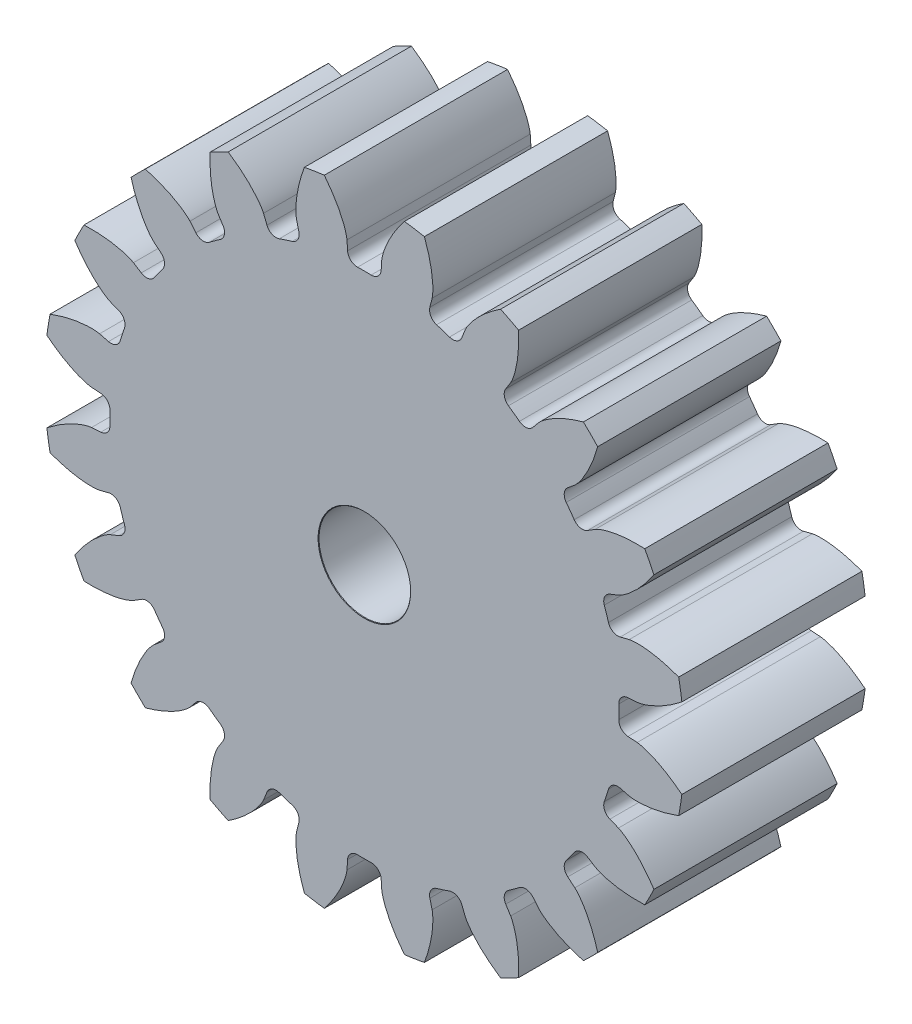
SolidWorks part; units mm, degrees
ref_plane "Front Plane" through (0, 0, 0) normal (0, 0, 1) x (1, 0, 0)
ref_plane "Top Plane" through (0, 0, 0) normal (0, 1, 0) x (1, 0, 0)
ref_plane "Right Plane" through (0, 0, 0) normal (1, 0, 0) x (0, 0, -1)
sketch "Sketch1" plane through (0, 0, 0) normal (0, 0, 1) x (1, 0, 0)
  line L0 (0, 0) -> (0, 15.875) construction
  line L1 (-5.1021, 17.732) -> (5.1021, 14.018) construction
  circle A0 centre (0, 0) radius 13.8906 construction
  circle A1 centre (0, 0) radius 17.4625 construction
  circle A2 centre (0, 0) radius 15.875 construction
  circle A3 centre (0, 0) radius 14.9176 construction
  point P8 (203.2, 0)
  point P13 (254, 0)
  dimension "OD | Outside Diameter" = 34.925
  dimension "Root Diameter" = 27.7812
  dimension "Gear Pitch Diameter" = 31.75
  dimension "Base Diameter" = 29.8352
  dimension "Pressure Angle" = 20
  dimension "Number of Teeth" = 508
  dimension "Gear Pitch | Diametral Pitch" = 406.4
sketch "Sketch2" plane through (0, 0, 0) normal (1, 0, 0) x (0, 0, -1)
  line L0 (-5, 0) -> (5, 0) construction
  point P2 (12.4625, 0)
  point P5 (21.1937, 0)
  point P6 (-12.4625, 0)
  dimension "Length" = 10
  dimension "D1" = 17.4625
  dimension "D2" = 26.1937
  dimension "D3" = 17.4625
sketch "Sketch3" plane through (0, 0, 0) normal (0, 0, 1) x (1, 0, 0)
  circle A0 centre (0, 0) radius 17.4625
  circle A1 centre (0, 0) radius 17.4625 construction
extrude "Boss-Extrude1" add sketch "Sketch3" against normal up to vertex (5 mm away) and the other way up to vertex (5 mm away) up to point (0, 0, -5) other way up to point (0, 0, 5)
sketch "Sketch4" plane through (0, 0, 0) normal (0, 0, 1) x (1, 0, 0)
  line L0 (0, 0) -> (13.8625, 0.8833) construction
  line L2 (0, 0) -> (13.8625, -0.8833) construction
  line L4 (13.8625, 0.8833) -> (14.8874, 0.9486)
  line L5 (14.8874, -0.9486) -> (13.8625, -0.8833)
  arc A0 (13.8625, 0.8833) -> (13.8625, -0.8833) centre (0, 0) cw
  arc A3 (17.3252, 2.1857) -> (17.3252, -2.1857) centre (0, 0) cw
  circle A4 centre (0, 0) radius 17.4625 construction
  spline S0 degree 4 poles (14.8874, 0.9486) (14.8915, 0.949) (14.9029, 0.95) (14.9244, 0.9526) (14.9595, 0.9578) (15.0039, 0.9657) (15.0613, 0.9774) (15.1285, 0.9932) (15.2021, 1.0126) (15.2819, 1.036) (15.3611, 1.0612) (15.4397, 1.0882) (15.5178, 1.1167) (15.612, 1.1532) (15.7243, 1.1996) (15.8547, 1.2576) (16.0015, 1.3281) (16.1499, 1.4047) (16.2948, 1.484) (16.44, 1.5687) (16.5795, 1.6539) (16.7229, 1.7469) (16.8547, 1.8351) (17.0006, 1.939) (17.1179, 2.0243) (17.2707, 2.1422) (17.3604, 2.2134) (17.4647, 2.2985) (17.5107, 2.3373) (17.539, 2.3612) knots 0 0 0 0 0 0.005377 0.015084 0.028532 0.04661 0.064855 0.092111 0.119476 0.146842 0.174209 0.201575 0.228941 0.256307 0.307035 0.361767 0.4165 0.471232 0.525964 0.580697 0.635429 0.690161 0.744894 0.799626 0.854358 0.909091 0.954545 1 1 1 1 1 construction
  spline S1 degree 4 poles (14.8874, 0.9486) (14.8915, 0.949) (14.9029, 0.95) (14.9244, 0.9526) (14.9595, 0.9578) (15.0039, 0.9657) (15.0613, 0.9774) (15.1285, 0.9932) (15.2021, 1.0126) (15.2819, 1.036) (15.3611, 1.0612) (15.4397, 1.0882) (15.5178, 1.1167) (15.612, 1.1532) (15.7243, 1.1996) (15.8547, 1.2576) (16.0015, 1.3281) (16.1499, 1.4047) (16.2948, 1.484) (16.44, 1.5687) (16.5795, 1.6539) (16.7229, 1.7469) (16.8547, 1.8351) (17.0006, 1.939) (17.1179, 2.0243) (17.2376, 2.1166) (17.2956, 2.1622) (17.3252, 2.1857) knots 0 0 0 0 0 0.005377 0.015084 0.028532 0.04661 0.064855 0.092111 0.119476 0.146842 0.174209 0.201575 0.228941 0.256307 0.307035 0.361767 0.4165 0.471232 0.525964 0.580697 0.635429 0.690161 0.744894 0.799626 0.854358 0.909091 0.909091 0.909091 0.909091 0.909091
  spline S2 degree 4 poles (14.8874, -0.9486) (14.8915, -0.949) (14.9029, -0.95) (14.9244, -0.9526) (14.9595, -0.9578) (15.0039, -0.9657) (15.0613, -0.9774) (15.1285, -0.9932) (15.2021, -1.0126) (15.2819, -1.036) (15.3611, -1.0612) (15.4397, -1.0882) (15.5178, -1.1167) (15.612, -1.1532) (15.7243, -1.1996) (15.8547, -1.2576) (16.0015, -1.3281) (16.1499, -1.4047) (16.2948, -1.484) (16.44, -1.5687) (16.5795, -1.6539) (16.7229, -1.7469) (16.8547, -1.8351) (17.0006, -1.939) (17.1179, -2.0243) (17.2707, -2.1422) (17.3604, -2.2134) (17.4647, -2.2985) (17.5107, -2.3373) (17.539, -2.3612) knots 0 0 0 0 0 0.005377 0.015084 0.028532 0.04661 0.064855 0.092111 0.119476 0.146842 0.174209 0.201575 0.228941 0.256307 0.307035 0.361767 0.4165 0.471232 0.525964 0.580697 0.635429 0.690161 0.744894 0.799626 0.854358 0.909091 0.954545 1 1 1 1 1 construction
  spline S3 degree 4 poles (14.8874, -0.9486) (14.8915, -0.949) (14.9029, -0.95) (14.9244, -0.9526) (14.9595, -0.9578) (15.0039, -0.9657) (15.0613, -0.9774) (15.1285, -0.9932) (15.2021, -1.0126) (15.2819, -1.036) (15.3611, -1.0612) (15.4397, -1.0882) (15.5178, -1.1167) (15.612, -1.1532) (15.7243, -1.1996) (15.8547, -1.2576) (16.0015, -1.3281) (16.1499, -1.4047) (16.2948, -1.484) (16.44, -1.5687) (16.5795, -1.6539) (16.7229, -1.7469) (16.8547, -1.8351) (17.0006, -1.939) (17.1179, -2.0243) (17.2376, -2.1166) (17.2956, -2.1622) (17.3252, -2.1857) knots 0 0 0 0 0 0.005377 0.015084 0.028532 0.04661 0.064855 0.092111 0.119476 0.146842 0.174209 0.201575 0.228941 0.256307 0.307035 0.361767 0.4165 0.471232 0.525964 0.580697 0.635429 0.690161 0.744894 0.799626 0.854358 0.909091 0.909091 0.909091 0.909091 0.909091
  dimension "D1" = 27.7812
extrude "Cut-Extrude1" cut sketch "Sketch4" against normal through all both and the other way through all
fillet "Fillet1" radius 0.5326 2 edges at (13.8625, -0.8833, 0) (13.8625, 0.8833, 0)
pattern_circular "CirPattern1" count 20 over 360 about axis through (0, 0, 5) along (0, 0, -1) of "Cut-Extrude1", "Fillet1"
sketch "Sketch6" plane through (0, 0, 5) normal (0, 0, 1) x (1, 0, 0)
  point P0 (0, 0)
hole_wizard "Ø5.0mm Dowel Hole1" positions "Sketch6" profile "Sketch7" hole size "Ø5.0" standard "ANSI Metric" end condition through all
sketch "Sketch7" plane through (0, 0, 5) normal (1, 0, 0) x (0, -1, 0)
  line L0 (0, 0) -> (0, 10)
  line L1 (0, 10) -> (2.5, 10)
  line L2 (2.5, 10) -> (2.5, 0.025)
  line L3 (2.5, 0.025) -> (2.525, 0)
  line L5 (2.525, 0) -> (0, 0)
  line L6 (-2.5, 0.025) -> (-2.525, 0) construction
  line L11 (0, -6.35) -> (0, 107.95) construction
  dimension "Thru Hole Dia." = 5
  dimension "Thru Hole Depth" = 10
  dimension "Near C'Sink Dia." = 5.05
  dimension "Near C'Sink Angle" = 90
equation "\"Root Diameter@Sketch1\"=\"Root Diameter\""
equation "\"OD | Outside Diameter@Sketch1\"=\"Outside Diameter\""
equation "\"D1@CirPattern1\"=\"Number of Teeth\""
equation "\"Diametral Pitch\"= 16"
equation "\"Number of Teeth\"= 20"
equation "\"Pressure Angle\"=20"
equation "\"Pitch Diameter\"= \"Number of Teeth\" / \"Diametral Pitch\""
equation "\"Base Diameter\"= \"Pitch Diameter\" * cos ( \"Pressure Angle\" )"
equation "\"Outside Diameter\"= ( \"Number of Teeth\" + 2 ) / \"Diametral Pitch\""
equation "\"Dedendum\"= 1.25 / \"Diametral Pitch\""
equation "\"Root Diameter\"= \"Pitch Diameter\" - ( 2 * \"Dedendum\" )"
equation "\"Pitch Angle\"= 360deg / \"Number of Teeth\""
equation "\"Alpha\"= sqr ( \"Pitch Diameter\" ^ 2 - \"Base Diameter\" ^ 2 ) / \"Base Diameter\" * 180 / PI - \"Pressure Angle\""
equation "\"Beta\"= ( \"Pitch Angle\" / 4 - \"Alpha\" )"
equation "\"Phi\"= sqr ( ( \"Outside Diameter\" / 2 ) ^ 2 - ( \"Base Diameter\" / 2 ) ^ 2 ) / ( \"Base Diameter\" / 2 )"
equation "\"Addendum\"= 1 / \"Diametral Pitch\""
equation "\"WorkingDepth\"= 2 / \"Diametral Pitch\""
equation "\"WholeDepth\"= 2.25 / \"Diametral Pitch\""
equation "\"Clearance\"= 0.25 / \"Diametral Pitch\""
equation "\"ToothThickness\"= ( pi * 2 ) / \"Diametral Pitch\""
equation "\"CircularPitch\"= pi / \"Diametral Pitch\""
equation "\"Number of Teeth@Sketch1\"=\"Number of Teeth\""
equation "\"Gear Pitch | Diametral Pitch@Sketch1\"=\"Diametral Pitch\""
equation "\"Pressure Angle@Sketch1\"=\"Pressure Angle\""
equation "\"Gear Pitch Diameter@Sketch1\"=\"Pitch Diameter\""
equation "\"Base Diameter@Sketch1\"=\"Base Diameter\""
equation "\"Fillet\"= \"Clearance\" * cos ( \"Pressure Angle\" ) * tan ( ( 90 + \"Pressure Angle\" ) / 2 )"
equation "\"D1@Fillet1\"=\"Fillet\""
equation "\"D1@Sketch4\"=if( \"Base Diameter\">\"Root Diameter\",\"Root Diameter\",\"Base Diameter\"-.00001)"
equation "\"D1@Sketch2\"=\"OD | Outside Diameter@Sketch1\"*2*0.5*0.5"
equation "\"D2@Sketch2\"=\"D1@Sketch2\"*1.5"
equation "\"D3@Sketch2\"=\"D1@Sketch2\""
equation "\"Length\"= 1cm"
equation "\"Length@Sketch2\"= \"Length\""
